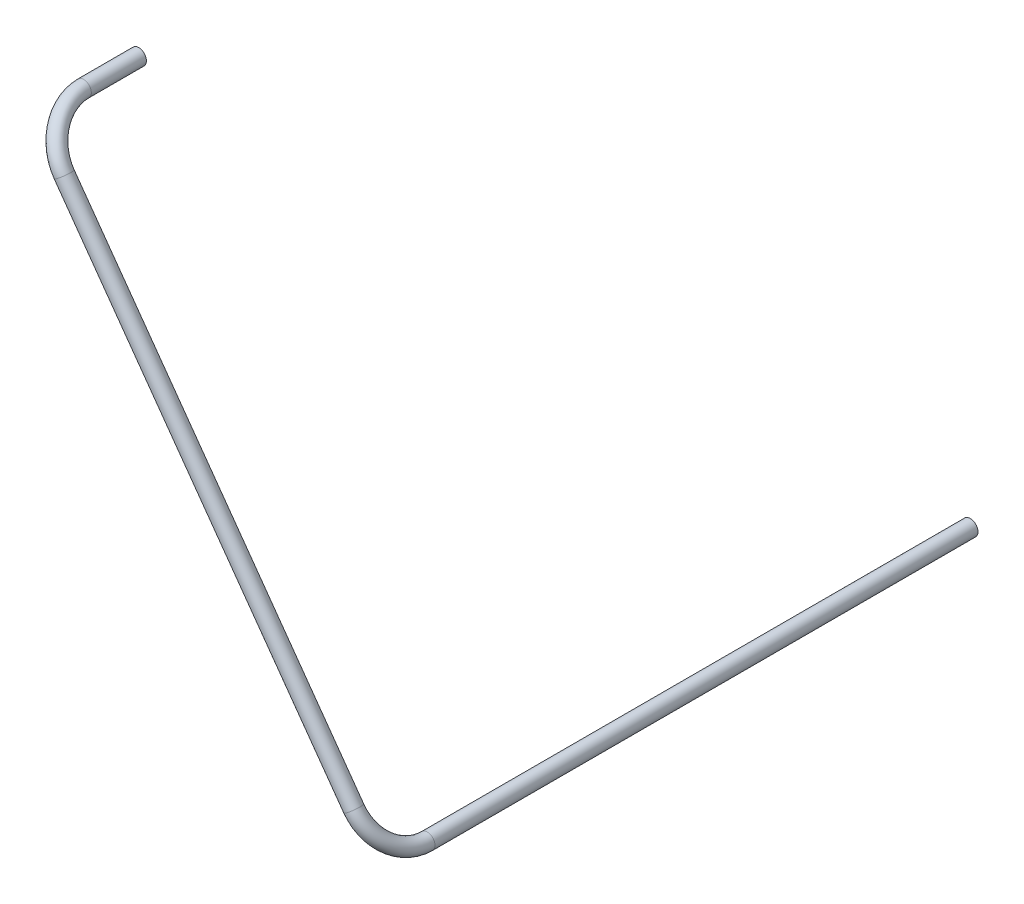
SolidWorks part; units mm, degrees
ref_plane "Front" through (0, 0, 0) normal (0, 0, 1) x (1, 0, 0)
ref_plane "Top" through (0, 0, 0) normal (0, 1, 0) x (1, 0, 0)
ref_plane "Side" through (0, 0, 0) normal (1, 0, 0) x (0, 0, -1)
sketch "PipeSketch" plane through (0, 0, 0) normal (0, 0, 1) x (1, 0, 0)
  circle A0 centre (0, 0) radius 6.35
  circle A1 centre (0, 0) radius 5.1054 construction
  dimension "OuterDiameter" = 12.7
  dimension "InnerDiameter" = 10.2108
sketch "FilterSketch" plane through (0, 0, 0) normal (0, 0, 1) x (1, 0, 0)
  circle A0 centre (0, 0) radius 6.35 construction
  dimension "NominalDiameter" = 12.7
sketch3d "3DSketch1"
  line L0 (0, 0, 10) -> (0, 0, 45.2248) construction
  line L1 (22.182, -30.9769, 83.3248) -> (259.8289, -362.8487, 83.3248) construction
  line L2 (282.0109, -393.8256, -390.3473) -> (282.0109, -393.8256, 45.2248) construction
  line L3 (0, 0, 0) -> (0, 0, 45.2248)
  line L4 (22.182, -30.9769, 83.3248) -> (259.8289, -362.8487, 83.3248)
  line L5 (282.0109, -393.8256, -400.3473) -> (282.0109, -393.8256, 45.2248)
  arc A0 (0, 0, 45.2248) -> (22.182, -30.9769, 83.3248) centre (22.182, -30.9769, 45.2248) ccw construction
  arc A1 (282.0109, -393.8256, 45.2248) -> (259.8289, -362.8487, 83.3248) centre (259.8289, -362.8487, 45.2248) ccw construction
  arc A2 (0, 0, 45.2248) -> (22.182, -30.9769, 83.3248) centre (22.182, -30.9769, 45.2248) ccw
  arc A3 (282.0109, -393.8256, 45.2248) -> (259.8289, -362.8487, 83.3248) centre (259.8289, -362.8487, 45.2248) ccw
  point P4 (53.1589, -8.795, 45.2248)
  point P6 (53.1589, -8.795, 45.2248)
  point P7 (228.852, -385.0307, 45.2248)
  point P12 (228.852, -385.0307, 45.2248)
sweep "ThinSweep" add profiles "PipeSketch" path "3DSketch1" parameters "WallThickness"=1.2446
ref_plane "Plane1" through (0, 0, 0) normal (0, 0, 1) x (1, 0, 0)
